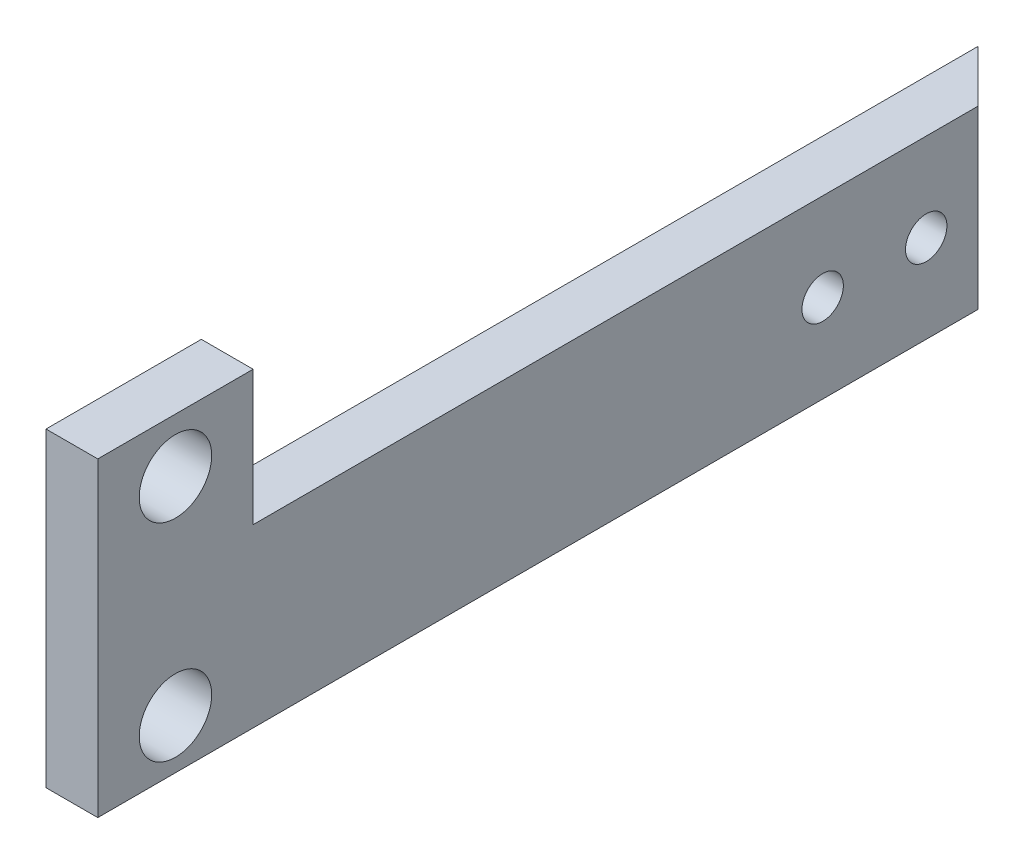
SolidWorks part; units mm, degrees
ref_plane "Front Plane" through (0, 0, 0) normal (0, 0, 1) x (1, 0, 0)
ref_plane "Top Plane" through (0, 0, 0) normal (0, 1, 0) x (1, 0, 0)
ref_plane "Right Plane" through (0, 0, 0) normal (1, 0, 0) x (0, 0, -1)
sketch "Croquis1" plane through (0, 0, 0) normal (0, 0, 1) x (1, 0, 0)
  line L1 (-2.5, -15) -> (2.5, -15)
  line L2 (-2.5, -15) -> (-2.5, 15)
  line L3 (-2.5, 15) -> (2.5, 15)
  line L4 (2.5, -15) -> (2.5, 15)
  line L5 (-2.5, -15) -> (2.5, 15) construction
  line L6 (-2.5, 15) -> (2.5, -15) construction
  point P0 (0, 0)
  dimension "D1" = 30
  dimension "D2" = 5
extrude "Saliente-Extruir1" add sketch "Croquis1" along normal blind 15
sketch "Croquis2" plane through (2.5, 0, 0) normal (1, 0, 0) x (0, 0, -1)
  line L0 (-15, 15) -> (0, 15) construction
  circle A0 centre (-7.5, 9.7951) radius 3.5
  circle A1 centre (-7.5, -10.2049) radius 3.5
  point P7 (-7.5, 15)
  dimension "D1" = 7
  dimension "D2" = 7
  dimension "D3" = 20
extrude "Cortar-Extruir1" cut sketch "Croquis2" against normal blind 15
sketch "Croquis3" plane through (0, 0, 0) normal (0, 0, -1) x (-1, 0, 0)
  line L1 (-2.5, 2) -> (2.5, 2)
  line L2 (-2.5, 2) -> (-2.5, -15)
  line L3 (-2.5, -15) -> (2.5, -15)
  line L4 (2.5, 2) -> (2.5, -15)
  line L5 (-2.5, 2) -> (2.5, -15) construction
  line L6 (-2.5, -15) -> (2.5, 2) construction
  point P0 (0, -6.5)
  dimension "D1" = 17
  dimension "D2" = 5
extrude "Saliente-Extruir2" add sketch "Croquis3" along normal blind 80
sketch "Croquis8" plane through (-2.5, 0, 0) normal (-1, 0, 0) x (0, 0, 1)
  line L0 (-80, -15) -> (-80, 2) construction
  line L1 (15, -15) -> (-80, -15) construction
  circle A0 centre (-55, -6.5) radius 2
  circle A1 centre (-65, -6.5) radius 2
  dimension "D1" = 4
  dimension "D2" = 4
  dimension "D3" = 10
  dimension "D4" = 15
  dimension "D5" = 8.5
  dimension "D6" = 8.5
extrude "Cortar-Extruir5" cut sketch "Croquis8" against normal blind 10
sketch "Croquis6" plane through (0, 2, 0) normal (0, 1, 0) x (1, 0, 0)
  line L13 (2.5, 75) -> (2.5, 70)
  line L14 (2.5, 80) -> (2.5, 0) construction
  line L15 (2.5, 70) -> (-2.5, 70)
  line L16 (-2.5, 80) -> (-2.5, 0) construction
  line L18 (-2.5, 80) -> (-2.5, 75)
  line L19 (-2.5, 80) -> (2.5, 80)
  line L20 (2.5, 80) -> (2.5, 75)
  line L21 (2.5, 70) -> (-2.5, 75)
  line L22 (-2.5, 75) -> (-2.5, 70)
  line M5 (2.5, 0) -> (2.5, 80)
  line M6 (2.5, 80) -> (-2.5, 80)
  line M7 (-2.5, 80) -> (-2.5, 0)
  dimension "D1" = 5
  dimension "D2" = 5
  dimension "D3" = 5
extrude "Cortar-Extruir4" cut sketch "Croquis6" against normal blind 30 contours L21 M5 M6 M7
